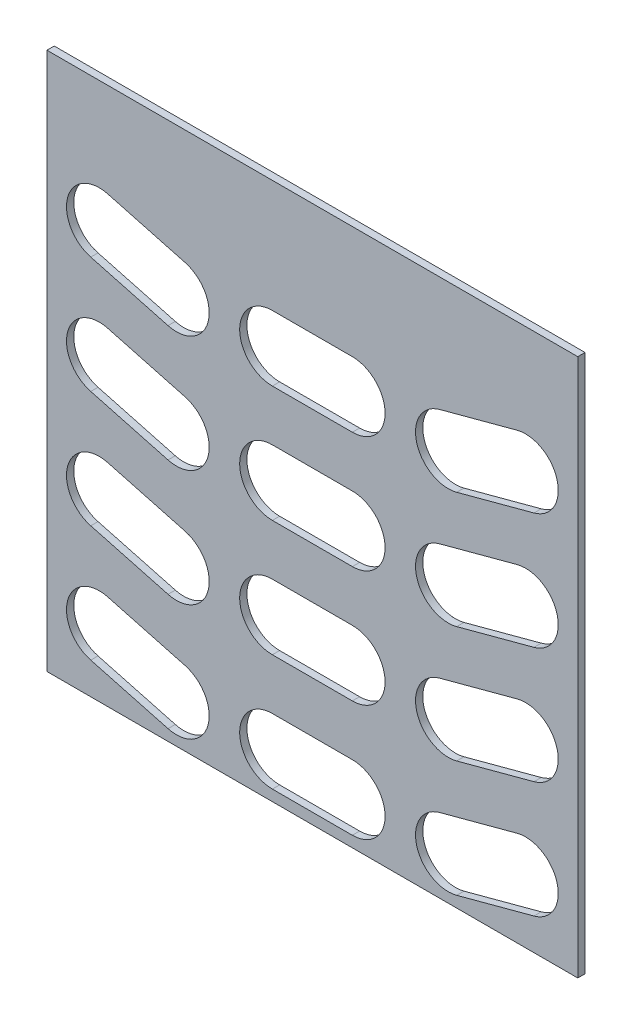
SolidWorks part; units mm, degrees
ref_plane "Front Plane" through (0, 0, 0) normal (0, 0, 1) x (1, 0, 0)
ref_plane "Top Plane" through (0, 0, 0) normal (0, 1, 0) x (1, 0, 0)
ref_plane "Right Plane" through (0, 0, 0) normal (1, 0, 0) x (0, 0, -1)
other "Configuration Table"
sketch "Sketch1" plane through (0, 0, 0) normal (0, 0, 1) x (1, 0, 0)
  line L0 (0, 0) -> (0, 37.3348) construction
  line L1 (-18.25, 34) -> (18.25, 34)
  line L2 (-18.25, 34) -> (-18.25, -3)
  line L3 (-18.25, -3) -> (18.25, -3)
  line L4 (18.25, 34) -> (18.25, -3)
  dimension "D1" = 36.5
  dimension "D2" = 37
  dimension "D3" = 3
extrude "Extrude1" add sketch "Sketch1" along normal blind 0.5
sketch "Sketch2" plane through (0, 0, 0) normal (0, 0, -1) x (-1, 0, 0)
  line L6 (-15.2386, 23.1854) -> (-9.926, 21.7619) construction
  line L7 (-8.7614, 26.1086) -> (-14.074, 27.5321) construction
  line L8 (-2.75, 21.75) -> (2.75, 21.75) construction
  line L9 (2.75, 26.25) -> (-2.75, 26.25) construction
  line L10 (9.926, 21.7619) -> (15.2386, 23.1854) construction
  line L11 (14.074, 27.5321) -> (8.7614, 26.1086) construction
  line L12 (-15.2386, 23.1854) -> (-9.926, 21.7619)
  line L13 (-8.7614, 26.1086) -> (-14.074, 27.5321)
  line L14 (-2.75, 21.75) -> (2.75, 21.75)
  line L15 (2.75, 26.25) -> (-2.75, 26.25)
  line L16 (9.926, 21.7619) -> (15.2386, 23.1854)
  line L17 (14.074, 27.5321) -> (8.7614, 26.1086)
  arc A6 (-14.074, 27.5321) -> (-15.2386, 23.1854) centre (-14.6563, 25.3588) ccw construction
  arc A7 (-9.926, 21.7619) -> (-8.7614, 26.1086) centre (-9.3437, 23.9352) ccw construction
  arc A8 (-2.75, 26.25) -> (-2.75, 21.75) centre (-2.75, 24) ccw construction
  arc A9 (2.75, 21.75) -> (2.75, 26.25) centre (2.75, 24) ccw construction
  arc A10 (8.7614, 26.1086) -> (9.926, 21.7619) centre (9.3437, 23.9352) ccw construction
  arc A11 (15.2386, 23.1854) -> (14.074, 27.5321) centre (14.6563, 25.3588) ccw construction
  arc A12 (-14.074, 27.5321) -> (-15.2386, 23.1854) centre (-14.6563, 25.3588) ccw
  arc A13 (-9.926, 21.7619) -> (-8.7614, 26.1086) centre (-9.3437, 23.9352) ccw
  arc A14 (-2.75, 26.25) -> (-2.75, 21.75) centre (-2.75, 24) ccw
  arc A15 (2.75, 21.75) -> (2.75, 26.25) centre (2.75, 24) ccw
  arc A16 (8.7614, 26.1086) -> (9.926, 21.7619) centre (9.3437, 23.9352) ccw
  arc A17 (15.2386, 23.1854) -> (14.074, 27.5321) centre (14.6563, 25.3588) ccw
extrude "Cut-Extrude1" cut sketch "Sketch2" against normal through all
pattern_linear "LPattern1" count 4 spacing 8 along (0, -1, 0) of "Cut-Extrude1"
